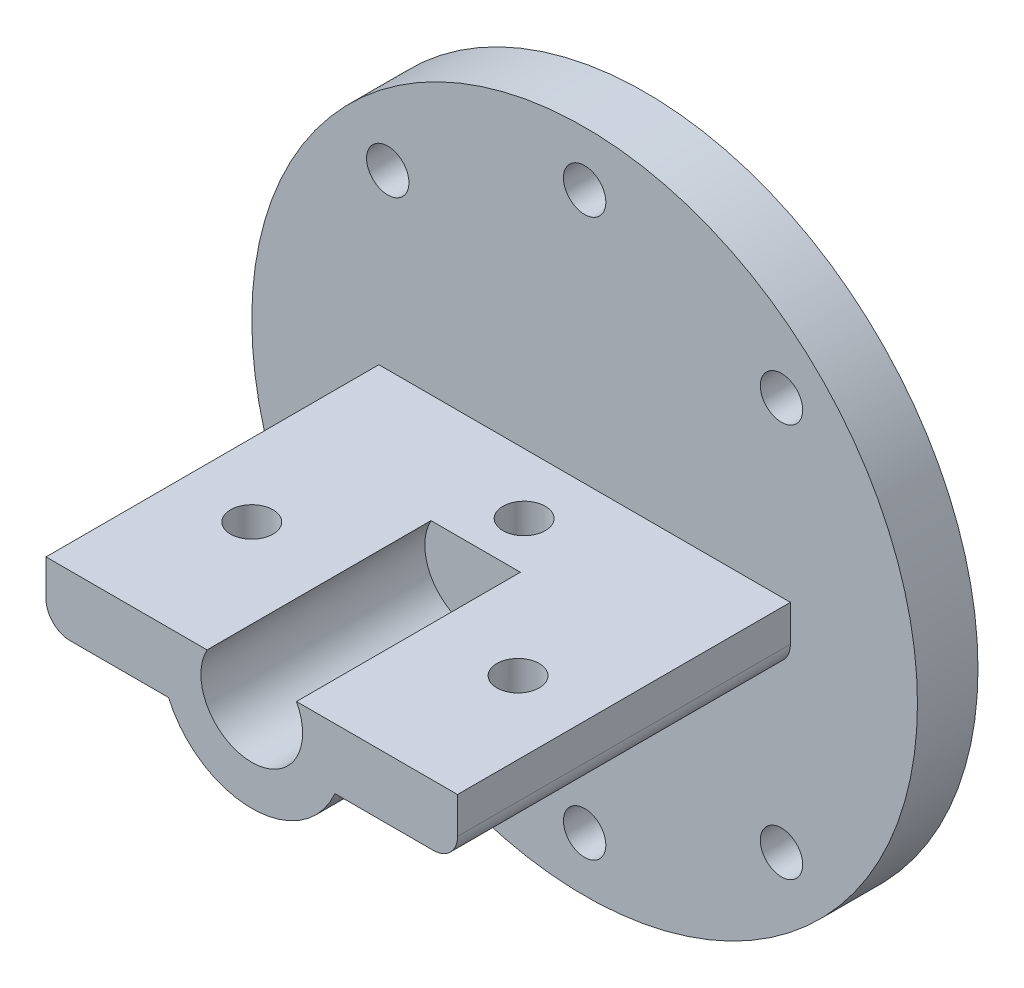
SolidWorks part; units mm, degrees
ref_plane "Front Plane" through (0, 0, 0) normal (0, 0, 1) x (1, 0, 0)
ref_plane "Top Plane" through (0, 0, 0) normal (0, 1, 0) x (1, 0, 0)
ref_plane "Right Plane" through (0, 0, 0) normal (1, 0, 0) x (0, 0, -1)
sketch "Sketch1" plane through (0, 0, 0) normal (0, 0, 1) x (1, 0, 0)
  line L0 (-2.7203, 3.2) -> (2.7203, 3.2)
  arc A0 (-2.7203, 3.2) -> (2.7203, 3.2) centre (0, 0) ccw
  circle A1 centre (0, 0) radius 7.5
  dimension "D1" = 4.2
  dimension "D3" = 15
  dimension "D2" = 3.2
extrude "Boss-Extrude1" add sketch "Sketch1" along normal blind 32.5
sketch "Sketch2" plane through (0, 0, 0) normal (0, 0, -1) x (-1, 0, 0)
  circle A0 centre (0, 0) radius 7.5
  circle A1 centre (0, 0) radius 27.5
  circle A2 centre (0, 23) radius 1.75
  circle A3 centre (16.2635, 16.2635) radius 1.75
  circle A5 centre (16.2635, -16.2635) radius 1.75
  circle A6 centre (0, -23) radius 1.75
  circle A7 centre (-16.2635, -16.2635) radius 1.75
  circle A9 centre (-16.2635, 16.2635) radius 1.75
  circle A10 centre (23, 0) radius 1.75 [skipped]
  circle A11 centre (-23, 0) radius 1.75 [skipped]
  point P22 (0, 0)
  dimension "D1" = 55
  dimension "D2" = 15
  dimension "D4" = 3.5
  dimension "D3" = 23
  dimension "D5" = 8
extrude "Boss-Extrude2" add sketch "Sketch2" against normal blind 5
sketch "Sketch3" plane through (0, 0, 32.5) normal (0, 0, 1) x (1, 0, 0)
  line L1 (-15, 8) -> (12, 8)
  line L2 (-15, 8) -> (-15, 2)
  line L3 (-15, 2) -> (12, 2)
  line L4 (12, 8) -> (12, 2)
  dimension "D1" = 27
  dimension "D2" = 15
  dimension "D3" = 2
  dimension "D4" = 6
extrude "Cut-Extrude1" cut sketch "Sketch3" against normal up to surface (27.5 mm away) up to face at (14.5135, 16.2635, 5)
sketch "Sketch4" plane through (0, 0, 0) normal (0, 0, -1) x (-1, 0, 0)
  line L0 (-2.7203, 3.2) -> (2.7203, 3.2) construction
  line L1 (-2.7203, 3.2) -> (2.7203, 3.2)
  arc A0 (-2.7203, 3.2) -> (2.7203, 3.2) centre (0, 0) ccw
extrude "Boss-Extrude3" add sketch "Sketch4" against normal blind 5
sketch "Sketch5" plane through (0, 0, 5) normal (0, 0, 1) x (1, 0, 0)
  line L0 (3.6932, 2) -> (7.2284, 2) construction
  line L1 (-3.6932, 2) -> (3.6932, 2)
  arc A0 (-3.6932, 2) -> (3.6932, 2) centre (0, 0) ccw
extrude "Boss-Extrude4" add sketch "Sketch5" along normal blind 9
sketch "Sketch6" plane through (0, 0, 5) normal (0, 0, 1) x (1, 0, 0)
  line L0 (-7.2284, 2) -> (-17, 2)
  line L1 (-17, 2) -> (-17, -3)
  line L2 (-17, -3) -> (-6.8739, -3)
  line L3 (6.8739, -3) -> (17, -3)
  line L4 (17, -3) -> (17, 2)
  line L5 (17, 2) -> (7.2284, 2)
  arc A0 (-7.2284, 2) -> (7.2284, 2) centre (0, 0) ccw construction
  arc A1 (-7.2284, 2) -> (7.2284, 2) centre (0, 0) ccw construction
  arc A5 (-7.2284, 2) -> (-6.8739, -3) centre (0, 0) ccw
  arc A6 (7.2284, 2) -> (6.8739, -3) centre (0, 0) cw
  dimension "D1" = 34
  dimension "D2" = 5
extrude "Boss-Extrude5" add sketch "Sketch6" along normal up to surface (27.5 mm away) up to face at (0, -1.925, 32.5)
sketch "Sketch7" plane through (0, 2, 0) normal (0, 1, 0) x (1, 0, 0)
  line L0 (-27.5, -5) -> (27.5, -5) construction
  line L1 (-17, -32.5) -> (-3.6932, -32.5) construction
  circle A0 centre (0, -10) radius 1.75
  circle A1 centre (-11, -21.5) radius 1.75
  circle A2 centre (11, -21.5) radius 1.75
  dimension "D4" = 3.5
  dimension "D1" = 5
  dimension "D2" = 11
  dimension "D3" = 11
  dimension "D5" = 11
extrude "Cut-Extrude2" cut sketch "Sketch7" against normal through all
fillet "Fillet1" radius 2 2 edges at (17, -3, 18.75) (-17, -3, 18.75)
